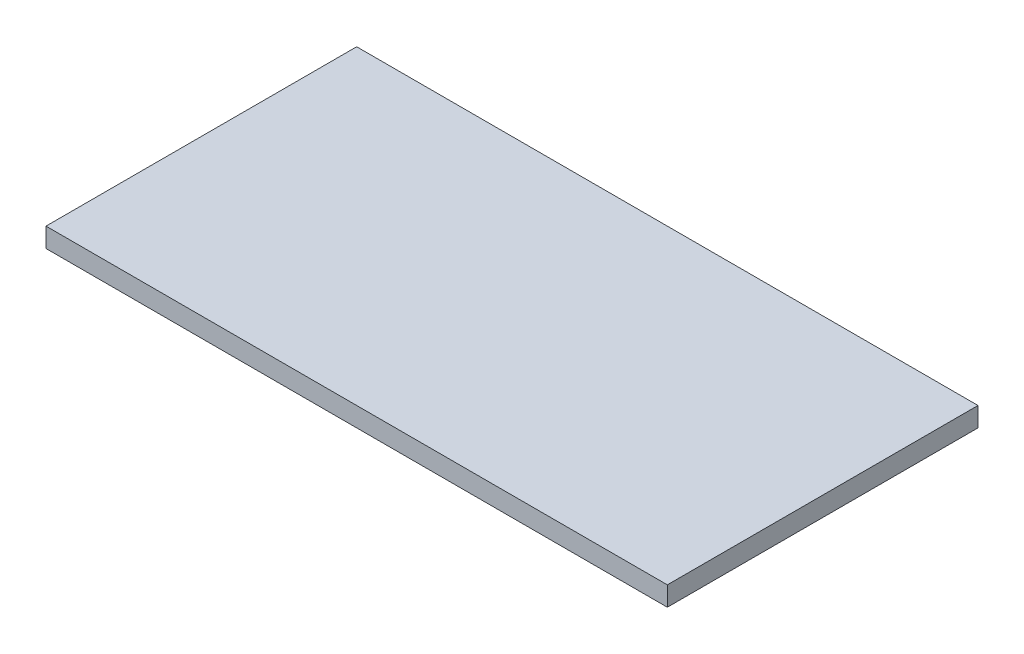
SolidWorks part; units mm, degrees
ref_plane "Front Plane" through (0, 0, 0) normal (0, 0, 1) x (1, 0, 0)
ref_plane "Top Plane" through (0, 0, 0) normal (0, 1, 0) x (1, 0, 0)
ref_plane "Right Plane" through (0, 0, 0) normal (1, 0, 0) x (0, 0, -1)
sketch "Sketch1" plane through (0, 0, 0) normal (0, 1, 0) x (1, 0, 0)
  line L1 (-50.8, -25.4) -> (50.8, -25.4)
  line L2 (-50.8, -25.4) -> (-50.8, 25.4)
  line L3 (-50.8, 25.4) -> (50.8, 25.4)
  line L4 (50.8, -25.4) -> (50.8, 25.4)
  line L5 (-50.8, -25.4) -> (50.8, 25.4) construction
  line L6 (-50.8, 25.4) -> (50.8, -25.4) construction
  point P0 (0, 0)
  dimension "D1" = 101.6
  dimension "D2" = 50.8
extrude "Boss-Extrude1" add sketch "Sketch1" along normal blind 3.175
